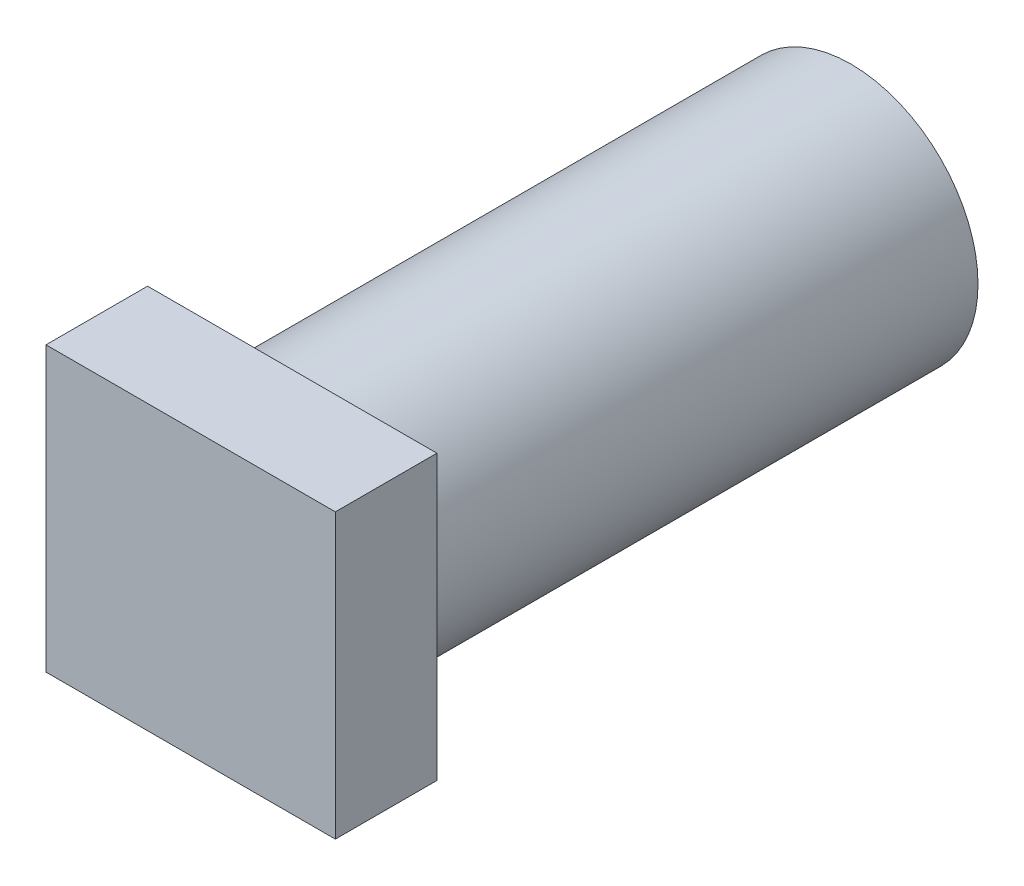
SolidWorks part; units mm, degrees
ref_plane "정면" through (0, 0, 0) normal (0, 0, 1) x (1, 0, 0)
ref_plane "윗면" through (0, 0, 0) normal (0, 1, 0) x (1, 0, 0)
ref_plane "우측면" through (0, 0, 0) normal (1, 0, 0) x (0, 0, -1)
sketch "스케치1" plane through (0, 0, 0) normal (0, 0, 1) x (1, 0, 0)
  circle A0 centre (0, 0) radius 2.5
  dimension "D1" = 5
extrude "보스-돌출1" add sketch "스케치1" along normal blind 11
sketch "스케치2" plane through (0, 0, 11) normal (0, 0, 1) x (1, 0, 0)
  line L1 (-2.848, 2.7901) -> (2.848, 2.7901)
  line L2 (-2.848, 2.7901) -> (-2.848, -2.7901)
  line L3 (-2.848, -2.7901) -> (2.848, -2.7901)
  line L4 (2.848, 2.7901) -> (2.848, -2.7901)
  line L5 (-2.848, 2.7901) -> (2.848, -2.7901) construction
  line L6 (-2.848, -2.7901) -> (2.848, 2.7901) construction
  point P0 (0, 0)
extrude "보스-돌출2" add sketch "스케치2" along normal blind 2
hole_wizard "M4 나사 구멍1" positions "스케치4" profile "스케치5" tap size "M4" standard "KS"
sketch "스케치4" plane through (0, 0, 0) normal (0, 0, -1) x (-1, 0, 0)
  point P0 (0, 0)
sketch "스케치5" plane through (0, 0, 0) normal (1, 0, 0) x (0, 1, 0)
  line L0 (0, 0) -> (0, 11.0914)
  line L1 (0, 11.0914) -> (1.65, 10.1)
  line L2 (1.65, 10.1) -> (1.65, 0.375)
  line L3 (1.65, 0.375) -> (2.025, 0)
  line L5 (2.025, 0) -> (0, 0)
  line L6 (-1.65, 0.375) -> (-2.025, 0) construction
  line L10 (0, 11.0914) -> (-1.65, 10.1) construction
  line L11 (0, -6.35) -> (0, 107.95) construction
  dimension "탭 드릴 지름" = 3.3
  dimension "탭 드릴 깊이" = 10.1
  dimension "표면 카운터싱크 지름" = 4.05
  dimension "표면 카운터싱크 각도" = 90
  dimension "드릴 각도" = 118
cosmetic thread "구멍 나사산1" parameters "D1"=8, "D2"=4
